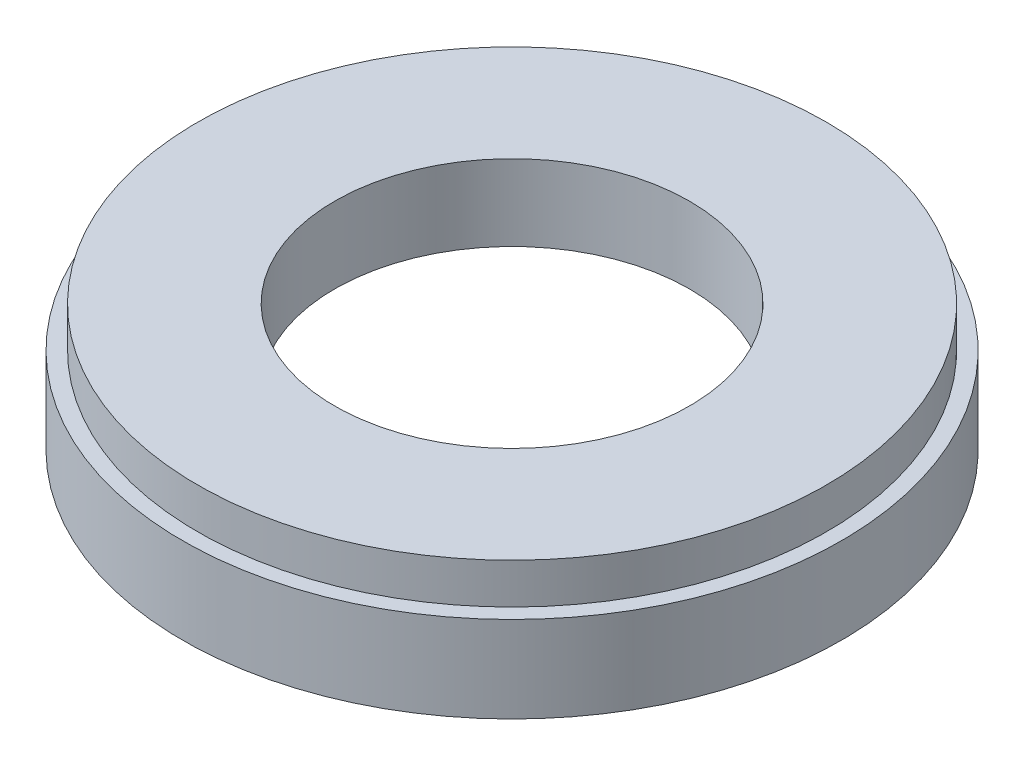
SolidWorks part; units mm, degrees
material "HYPALON"
ref_plane "Front Plane" through (0, 0, 0) normal (0, 0, 1) x (1, 0, 0)
ref_plane "Top Plane" through (0, 0, 0) normal (0, 1, 0) x (1, 0, 0)
ref_plane "Right Plane" through (0, 0, 0) normal (1, 0, 0) x (0, 0, -1)
sketch "Szkic1" plane through (0, 0, 0) normal (0, 0, 1) x (1, 0, 0)
  line L0 (0, 0) -> (-65, 0)
  line L1 (-65, 0) -> (-65, 15)
  line L2 (-65, 15) -> (-35, 15)
  line L3 (-35, 15) -> (-35, 0)
  line L4 (0, 0) -> (0, 23.5461)
  line L6 (-65, 0) -> (-62, 0)
  line L7 (-65, 0) -> (-65, -10)
  line L8 (-65, -10) -> (-62, -10)
  line L9 (-62, 0) -> (-62, -10)
  line L10 (-65, 15) -> (-62, 15)
  line L11 (-65, 15) -> (-65, 7)
  line L12 (-65, 7) -> (-62, 7)
  line L13 (-62, 15) -> (-62, 7)
  dimension "D1" = 65
  dimension "D2" = 15
  dimension "D3" = 35
  dimension "D4" = 3
  dimension "D5" = 8
  dimension "D6" = 10
  dimension "D7" = 3
revolve "Obrót1" add sketch "Szkic1" angle 360 about L4
